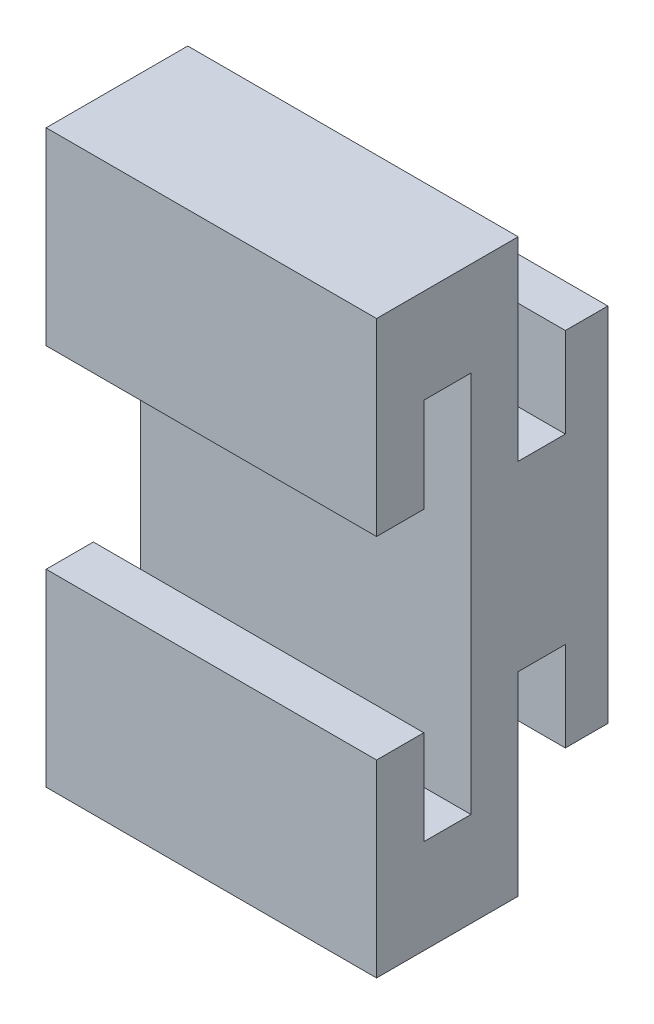
SolidWorks part; units mm, degrees
ref_plane "Front Plane" through (0, 0, 0) normal (0, 0, 1) x (1, 0, 0)
ref_plane "Top Plane" through (0, 0, 0) normal (0, 1, 0) x (1, 0, 0)
ref_plane "Right Plane" through (0, 0, 0) normal (1, 0, 0) x (0, 0, -1)
sketch "Sketch1" plane through (0, 0, 0) normal (0, 0, 1) x (1, 0, 0)
  line L1 (-8.89, -15.367) -> (8.89, -15.367)
  line L2 (-8.89, -15.367) -> (-8.89, 15.367)
  line L3 (-8.89, 15.367) -> (8.89, 15.367)
  line L4 (8.89, -15.367) -> (8.89, 15.367)
  line L5 (-8.89, -15.367) -> (8.89, 15.367) construction
  line L6 (-8.89, 15.367) -> (8.89, -15.367) construction
  point P0 (0, 0)
  dimension "D1" = 30.734
  dimension "D2" = 17.78
extrude "Boss-Extrude1" add sketch "Sketch1" along normal blind 2.54 contours L2 L3 L4 L1
sketch "Sketch2" plane through (0, 0, 2.54) normal (0, 0, 1) x (1, 0, 0)
  line L0 (8.89, -15.367) -> (8.89, 15.367) construction
  line L1 (-8.89, -15.367) -> (8.89, -15.367)
  line L2 (-8.89, -15.367) -> (-8.89, -10.287)
  line L3 (-8.89, -10.287) -> (8.89, -10.287)
  line L4 (8.89, -15.367) -> (8.89, -10.287)
  dimension "D1" = 5.08
extrude "Boss-Extrude2" add sketch "Sketch2" along normal blind 5.08
sketch "Sketch3" plane through (0, -10.287, 0) normal (0, 1, 0) x (1, 0, 0)
  line L0 (8.89, -7.62) -> (8.89, -2.54) construction
  line L1 (-8.89, -7.62) -> (8.89, -7.62)
  line L2 (-8.89, -7.62) -> (-8.89, -5.08)
  line L3 (-8.89, -5.08) -> (8.89, -5.08)
  line L4 (8.89, -7.62) -> (8.89, -5.08)
extrude "Boss-Extrude3" add sketch "Sketch3" along normal blind 5.08
ref_plane "Plane1" through (0, 0, 0) normal (0, 1, 0) x (1, 0, 0)
mirror "Mirror1" about plane through (0, 0, 0) normal (0, 1, 0) of "Boss-Extrude2", "Boss-Extrude3"
sketch "Sketch4" plane through (0, 0, 0) normal (0, 0, -1) x (-1, 0, 0)
  line L0 (-8.89, -15.367) -> (-8.89, 15.367) construction
  line L1 (-8.89, 4.9022) -> (8.89, 4.9022)
  line L2 (-8.89, 4.9022) -> (-8.89, -4.9022)
  line L3 (-8.89, -4.9022) -> (8.89, -4.9022)
  line L4 (8.89, 4.9022) -> (8.89, -4.9022)
  line L5 (8.89, -15.367) -> (8.89, 15.367) construction
  line L6 (8.89, 15.367) -> (-8.89, 15.367) construction
  line L7 (8.89, -15.367) -> (-8.89, -15.367) construction
  dimension "D1" = 10.4648
  dimension "D2" = 10.4648
extrude "Boss-Extrude4" add sketch "Sketch4" along normal blind 4.826
sketch "Sketch5" plane through (0, 4.9022, 0) normal (0, 1, 0) x (1, 0, 0)
  line L0 (8.89, 4.826) -> (8.89, 0) construction
  line L1 (-8.89, 4.826) -> (8.89, 4.826)
  line L2 (-8.89, 4.826) -> (-8.89, 2.54)
  line L3 (-8.89, 2.54) -> (8.89, 2.54)
  line L4 (8.89, 4.826) -> (8.89, 2.54)
  dimension "D1" = 2.286
extrude "Boss-Extrude5" add sketch "Sketch5" along normal blind 4.826
mirror "Mirror2" about plane through (0, 0, 0) normal (0, 1, 0) of "Boss-Extrude4", "Boss-Extrude5"
